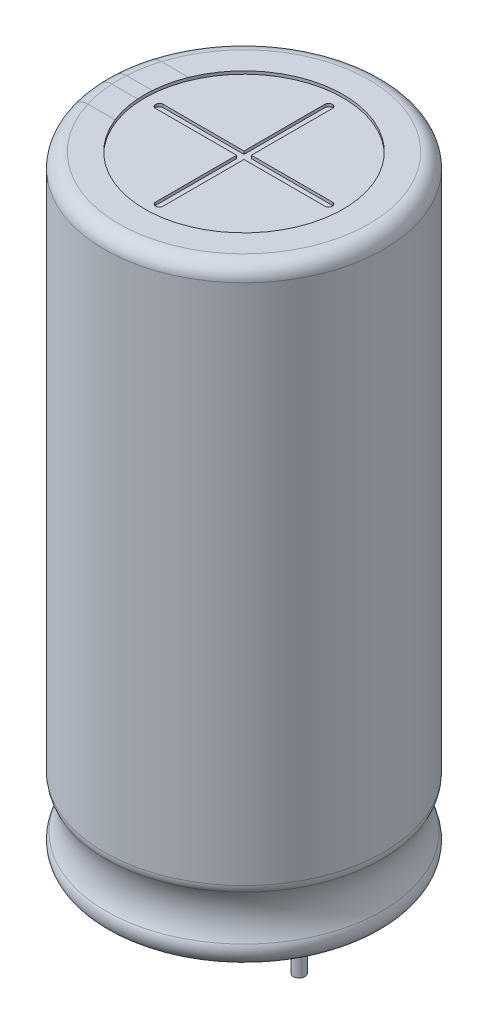
SolidWorks part; units mm, degrees
ref_plane "Front" through (0, 0, 0) normal (0, 0, 1) x (1, 0, 0)
ref_plane "Top" through (0, 0, 0) normal (0, 1, 0) x (1, 0, 0)
ref_plane "Right" through (0, 0, 0) normal (1, 0, 0) x (0, 0, -1)
sketch "Эскиз2" plane through (0, 0, 0) normal (0, 0, 1) x (1, 0, 0)
  line L0 (0, 0) -> (8.5, 0)
  line L1 (9.5, 5) -> (9.5, 40.5)
  line L2 (8.5, 41.5) -> (0, 41.5)
  line L3 (0, 0) -> (0, 41.5) construction
  line L4 (0, 0) -> (0, 41.5)
  arc A0 (8.5, 0) -> (9.5, 1) centre (8.5, 1) ccw
  arc A1 (9.5, 40.5) -> (8.5, 41.5) centre (8.5, 40.5) ccw
  arc A2 (9.5, 1) -> (9.3824, 1.4706) centre (8.5, 1) ccw
  arc A3 (9.3824, 4.5294) -> (9.3824, 1.4706) centre (12.25, 3) ccw
  arc A4 (9.3824, 4.5294) -> (9.5, 5) centre (8.5, 5) ccw
  point P7 (9.5, 0)
  point P10 (9.5, 41.5)
  point P12 (8.7044, 2.0685)
  point P14 (9.4697, 1)
  point P15 (9.3255, 1.5645)
  point P18 (9.3375, 2.243)
  point P19 (9.1788, 2.1839)
  point P20 (9.2951, 1.5645)
  point P21 (0, 0)
  point P22 (9.5, 2.9949)
  point P24 (9.3022, 3.1694)
  point P25 (9.3284, 2.2287)
  point P26 (0, 0)
  point P27 (9.0616, 3.6498)
  point P29 (0, 0)
  point P30 (0, 0)
  point P31 (9, 3)
  dimension "D3" = 1
  dimension "D4" = 0.5
  dimension "D1" = 9.5
  dimension "D2" = 41.5
  dimension "D5" = 4
revolve "Повернуть1" add sketch "Эскиз2" angle 360 about L3
sketch "Эскиз3" plane through (0, 41.5, 0) normal (0, 1, 0) x (1, 0, 0)
  circle A0 centre (0, 0) radius 6.75
  dimension "D1" = 13.5
extrude "Вырез-Вытянуть1" cut sketch "Эскиз3" against normal blind 0.2
sketch "Эскиз4" plane through (0, 41.3, 0) normal (0, 1, 0) x (1, 0, 0)
  line L0 (-0.25, -0.25) -> (-0.25, -5.76)
  line L1 (-0.01, 6) -> (0.01, 6)
  line L2 (-0.25, 5.76) -> (-0.25, 0.25)
  line L3 (-0.01, -6) -> (0.01, -6)
  line L4 (0.25, 5.76) -> (0.25, 0.25)
  line L5 (-5.76, 0.25) -> (-0.25, 0.25)
  line L6 (-6, 0.01) -> (-6, -0.01)
  line L7 (-5.76, -0.25) -> (-0.25, -0.25)
  line L8 (6, 0.01) -> (6, -0.01)
  line L9 (0.25, 0.25) -> (5.76, 0.25)
  line L10 (0.25, -0.25) -> (0.25, -5.76)
  line L11 (0.25, -0.25) -> (5.76, -0.25)
  arc A0 (0.01, 6) -> (0.25, 5.76) centre (0.01, 5.76) cw
  arc A1 (-0.01, 6) -> (-0.25, 5.76) centre (-0.01, 5.76) ccw
  arc A2 (5.76, -0.25) -> (6, -0.01) centre (5.76, -0.01) ccw
  arc A3 (5.76, 0.25) -> (6, 0.01) centre (5.76, 0.01) cw
  arc A4 (0.01, -6) -> (0.25, -5.76) centre (0.01, -5.76) ccw
  arc A5 (-0.25, -5.76) -> (-0.01, -6) centre (-0.01, -5.76) ccw
  arc A6 (-6, -0.01) -> (-5.76, -0.25) centre (-5.76, -0.01) ccw
  arc A7 (-5.76, 0.25) -> (-6, 0.01) centre (-5.76, 0.01) ccw
  point P15 (0.25, 6)
  point P18 (-0.25, 6)
  point P23 (6, 0.25)
  point P26 (0.25, -6)
  point P31 (-6, -0.25)
  point P34 (-6, 0.25)
  dimension "D9" = 0.24
  dimension "D1" = 0.5
  dimension "D2" = 0.5
  dimension "D3" = 0.25
  dimension "D4" = 0.25
  dimension "D5" = 12
  dimension "D6" = 6
  dimension "D7" = 12
  dimension "D8" = 6
extrude "Вырез-Вытянуть2" cut sketch "Эскиз4" against normal blind 0.2
sketch "Эскиз5" plane through (0, 0, 0) normal (0, -1, 0) x (1, 0, 0)
  circle A0 centre (0, 0) radius 7.3
  dimension "D1" = 14.6
extrude "Вырез-Вытянуть3" cut sketch "Эскиз5" against normal blind 0.2
sketch "Эскиз6" plane through (0, 0.2, 0) normal (0, -1, 0) x (1, 0, 0)
  line L1 (-5.3376, 2) -> (5.3376, 2)
  line L3 (-5.3376, -2) -> (5.3376, -2)
  arc A0 (-5.3376, -2) -> (5.3376, -2) centre (0, 0) ccw
  arc A1 (5.3376, 2) -> (-5.3376, 2) centre (0, 0) ccw
  dimension "D1" = 11.4
  dimension "D2" = 4
  dimension "D3" = 2
extrude "Бобышка-Вытянуть1" add sketch "Эскиз6" along normal blind 1.2
sketch "Эскиз7" plane through (0, 0.2, 0) normal (0, -1, 0) x (1, 0, 0)
  circle A0 centre (-3.75, 0) radius 0.4
  circle A1 centre (3.75, 0) radius 0.4
  point P4 (0, 0)
  dimension "D1" = 0.8
  dimension "D2" = 0.8
  dimension "D3" = 7.5
  dimension "D4" = 3.75
extrude "Бобышка-Вытянуть2" add sketch "Эскиз7" along normal blind 5.2
sketch "Эскиз8" plane through (0, 0, 0) normal (1, 0, 0) x (0, 0, -1)
  line L0 (-28.6801, 37.7918) -> (28.8385, 9.8656)
  line L1 (-21.6835, 38.3327) -> (15.727, 1.1093)
  point P4 (15.727, 1.1093)
  point P5 (-21.6835, 38.3327)
ref_plane "Плоскость1" through (9.5, 0, 0) normal (1, 0, 0) x (0, 0, -1)
sketch "Эскиз9" plane through (0, 0, 0) normal (1, 0, 0) x (0, 0, -1)
  line L0 (-0.4, -5) -> (0.4, -5) construction
  line L1 (-2.5, 45) -> (2.5, 45)
  line L2 (-2.5, 45) -> (-2.5, -5)
  line L3 (-2.5, -5) -> (2.5, -5)
  line L4 (2.5, 45) -> (2.5, -5)
  line L5 (-0.5, 39) -> (-0.5, 36)
  line L6 (-0.5, 44) -> (0.5, 44)
  line L7 (-0.5, 44) -> (-0.5, 41)
  line L8 (-0.5, 41) -> (0.5, 41)
  line L9 (0.5, 44) -> (0.5, 41)
  line L10 (-0.5, 39) -> (0.5, 39)
  line L11 (0.5, 39) -> (0.5, 36)
  line L12 (-0.5, 36) -> (0.5, 36)
  line L13 (-0.5, 34) -> (-0.5, 31)
  line L14 (-0.5, 34) -> (0.5, 34)
  line L15 (0.5, 34) -> (0.5, 31)
  line L16 (-0.5, 31) -> (0.5, 31)
  line L17 (-0.5, 29) -> (-0.5, 26)
  line L18 (-0.5, 29) -> (0.5, 29)
  line L19 (0.5, 29) -> (0.5, 26)
  line L20 (-0.5, 26) -> (0.5, 26)
  line L21 (-0.5, 24) -> (-0.5, 21)
  line L22 (-0.5, 24) -> (0.5, 24)
  line L23 (0.5, 24) -> (0.5, 21)
  line L24 (-0.5, 21) -> (0.5, 21)
  line L25 (-0.5, 19) -> (-0.5, 16)
  line L26 (-0.5, 19) -> (0.5, 19)
  line L27 (0.5, 19) -> (0.5, 16)
  line L28 (-0.5, 16) -> (0.5, 16)
  line L29 (-0.5, 14) -> (-0.5, 11)
  line L30 (-0.5, 14) -> (0.5, 14)
  line L31 (0.5, 14) -> (0.5, 11)
  line L32 (-0.5, 11) -> (0.5, 11)
  line L33 (-0.5, 9) -> (-0.5, 6)
  line L34 (-0.5, 9) -> (0.5, 9)
  line L35 (0.5, 9) -> (0.5, 6)
  line L36 (-0.5, 6) -> (0.5, 6)
  line L37 (-0.5, 4) -> (-0.5, 1)
  line L38 (-0.5, 4) -> (0.5, 4)
  line L39 (0.5, 4) -> (0.5, 1)
  line L40 (-0.5, 1) -> (0.5, 1)
  line L41 (-0.5, -1) -> (-0.5, -4)
  line L42 (-0.5, -1) -> (0.5, -1)
  line L43 (0.5, -1) -> (0.5, -4)
  line L44 (-0.5, -4) -> (0.5, -4)
  point P11 (0, 44)
  point P12 (0, 45)
  dimension "D1" = 5
  dimension "D2" = 2.5
  dimension "D3" = 50
  dimension "D4" = 3
  dimension "D5" = 1
  dimension "D6" = 1
  dimension "D8" = 5
  dimension "D7" = 10
split line "Разделяющая линия5"
